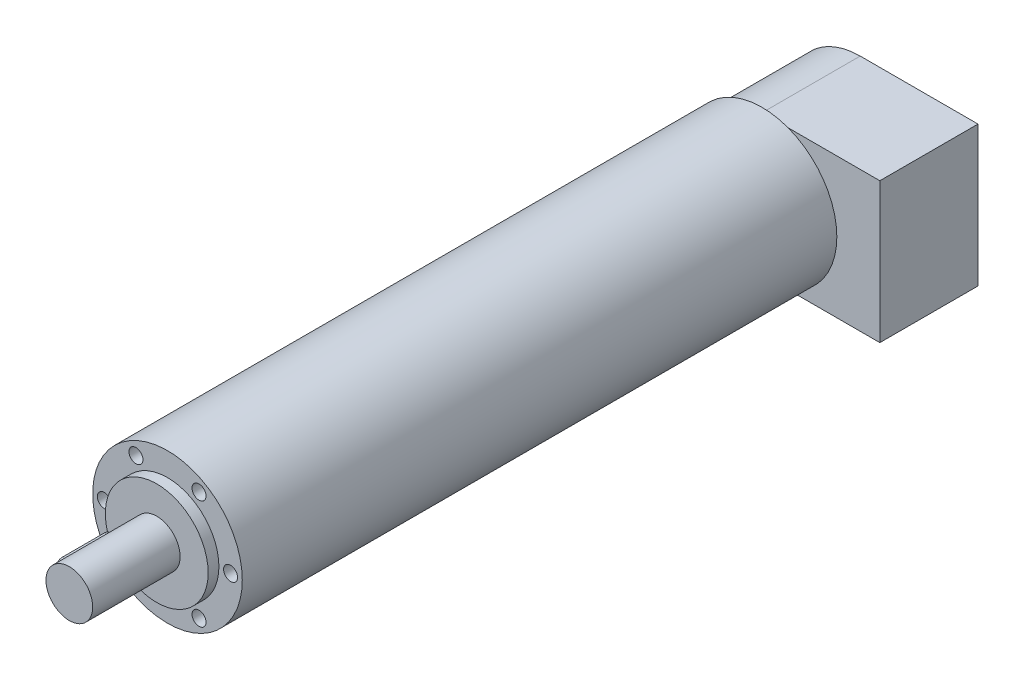
SolidWorks part; units mm, degrees
material "Titanium Ti-8Mn, Annealed"
ref_plane "Front" through (0, 0, 0) normal (0, 0, 1) x (1, 0, 0)
ref_plane "Top" through (0, 0, 0) normal (0, 1, 0) x (1, 0, 0)
ref_plane "Right" through (0, 0, 0) normal (1, 0, 0) x (0, 0, -1)
sketch "Sketch1" plane through (0, 0, 0) normal (0, 0, 1) x (1, 0, 0)
  circle A0 centre (0, 0) radius 15
  dimension "D1" = 30
extrude "Boss-Extrude1" add sketch "Sketch1" along normal blind 21
sketch "Sketch2" plane through (0, 0, 0) normal (1, 0, 0) x (0, 0, -1)
  line L0 (0, -15) -> (0, 15) construction
  line L1 (-21, -15) -> (0, -15)
  line L2 (-21, -15) -> (-21, 15)
  line L3 (-21, 15) -> (0, 15)
  line L4 (0, -15) -> (0, 15)
  line L5 (-21, -15) -> (0, 15) construction
  line L6 (-21, 15) -> (0, -15) construction
  point P0 (-10.5, 0)
  dimension "D1" = 21
  dimension "D2" = 30
extrude "Boss-Extrude2" add sketch "Sketch2" along normal blind 25.2
sketch "Sketch3" plane through (0, 0, 21) normal (0, 0, 1) x (1, 0, 0)
  circle A0 centre (0, 0) radius 16
  dimension "D1" = 32
extrude "Boss-Extrude3" add sketch "Sketch3" along normal blind 127.2
sketch "Sketch4" plane through (0, 0, 148.2) normal (0, 0, 1) x (1, 0, 0)
  circle A0 centre (0, 0) radius 11
  dimension "D1" = 22
extrude "Boss-Extrude4" add sketch "Sketch4" along normal blind 2.3
sketch "Sketch6" plane through (0, 0, 150.5) normal (0, 0, 1) x (1, 0, 0)
  circle A0 centre (0, 0) radius 5
  dimension "D1" = 10
extrude "Boss-Extrude6" add sketch "Sketch6" along normal blind 18.7
sketch "Sketch5" plane through (0, 0, 0) normal (1, 0, 0) x (0, 0, -1)
  line L0 (-155.7, 1.5) -> (-164.7, 1.5)
  line L1 (-164.7, -1.5) -> (-155.7, -1.5)
  line L4 (-169.2, 5) -> (-169.2, -5) construction
  arc A0 (-164.7, 1.5) -> (-164.7, -1.5) centre (-164.7, 0) ccw
  arc A1 (-155.7, -1.5) -> (-155.7, 1.5) centre (-155.7, 0) ccw
  dimension "D1" = 1.5
  dimension "D3" = 4.5
  dimension "D2" = 9
extrude "Boss-Extrude7" add sketch "Sketch5" against normal blind 6
sketch "Sketch7" plane through (0, 0, 148.2) normal (0, 0, 1) x (1, 0, 0)
  line L0 (50, 0) -> (-50, 0) construction
  circle A0 centre (13.5, 0) radius 1.5
  circle A1 centre (0, 0) radius 16 construction
  dimension "D1" = 3
  dimension "D2" = 13.5
extrude "Cut-Extrude1" cut sketch "Sketch7" against normal blind 10
pattern_circular "CirPattern1" count 6 over 360 about axis through (0, 0, 0) along (0, 0, 1) of "Cut-Extrude1"
